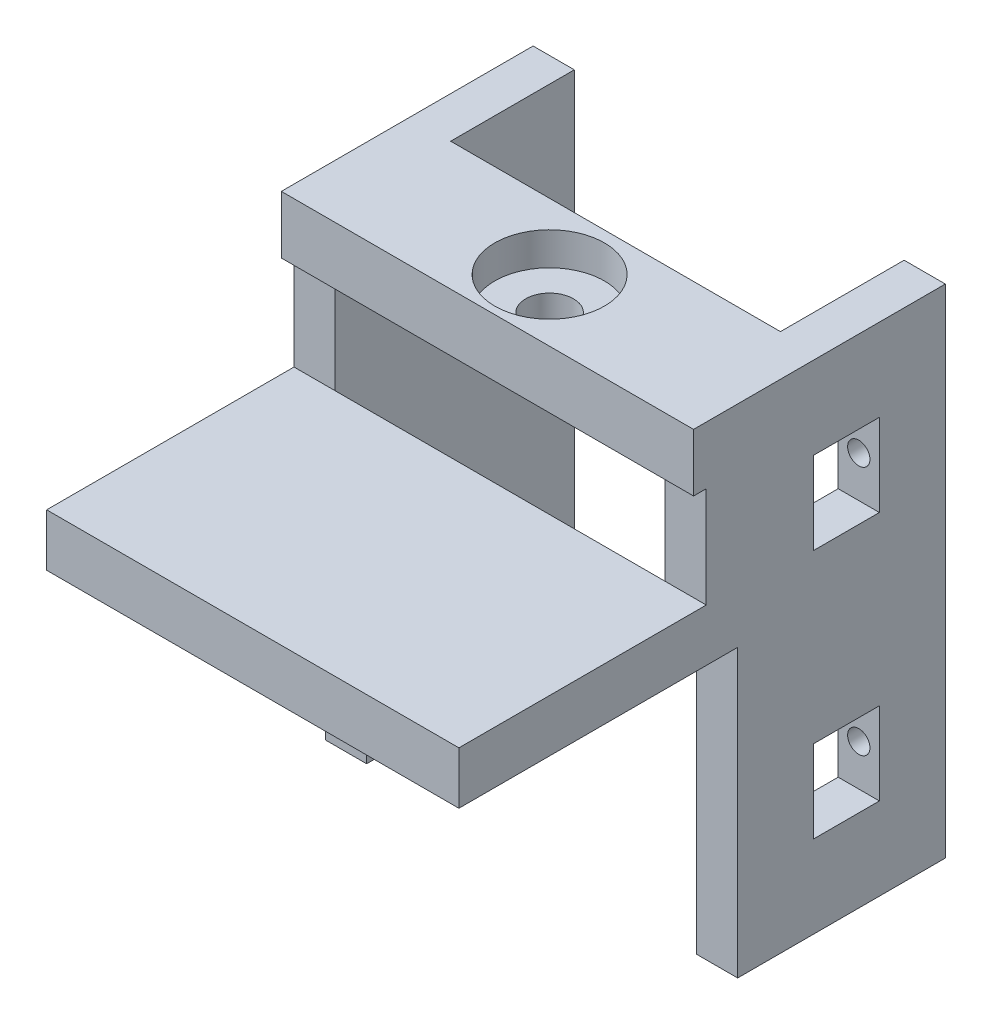
SolidWorks part; units mm, degrees
material "Copper"
ref_plane "Front Plane" through (0, 0, 0) normal (0, 0, 1) x (1, 0, 0)
ref_plane "Top Plane" through (0, 0, 0) normal (0, 1, 0) x (1, 0, 0)
ref_plane "Right Plane" through (0, 0, 0) normal (1, 0, 0) x (0, 0, -1)
sketch "Sketch1" plane through (0, 0, 0) normal (0, 1, 0) x (1, 0, 0)
  line L1 (0, 0) -> (50, 0)
  line L2 (0, 0) -> (0, 30)
  line L3 (0, 30) -> (50, 30)
  line L4 (50, 0) -> (50, 30)
  dimension "D1" = 50
  dimension "D2" = 30
extrude "Boss-Extrude1" add sketch "Sketch1" along normal blind 7
sketch "Sketch2" plane through (50, 0, 0) normal (1, 0, 0) x (0, 0, -1)
  line L0 (30, 7) -> (57, 7)
  line L1 (57, 7) -> (57, -53.3)
  line L2 (57, -53.3) -> (30, -53.3)
  line L3 (30, -53.3) -> (30, 7)
  dimension "D2" = 60.3
  dimension "D3" = 27
extrude "Boss-Extrude2" add sketch "Sketch2" against normal blind 5
ref_plane "Plane1" through (25, 0, 0) normal (1, 0, 0) x (0, 0, -1)
mirror "Mirror1" about plane through (25, 0, 0) normal (1, 0, 0) of "Boss-Extrude2"
sketch "Sketch3" plane through (0, 0, -30) normal (0, 0, -1) x (-1, 0, 0)
  line L4 (-5, 0) -> (-5, 7)
  line L5 (-5, 7) -> (-45, 7)
  line L6 (-45, 7) -> (-45, 0)
  line L7 (-45, 0) -> (-5, 0)
  line L8 (-5, 0) -> (-5, 7)
  line L9 (-5, 7) -> (-45, 7)
  line L10 (-45, 7) -> (-45, 0)
  line L11 (-45, 0) -> (-5, 0)
  dimension "D1" = 0
extrude "Boss-Extrude3" add sketch "Sketch3" along normal blind 12
sketch "Sketch4" plane through (0, 7, 0) normal (0, 1, 0) x (1, 0, 0)
  line L0 (25, 34) -> (25, 0) construction
  line L1 (0, 0) -> (50, 0) construction
  circle A0 centre (25, 34) radius 6.65
  dimension "D1" = 13.3
  dimension "D2" = 34
extrude "Cut-Extrude1" cut sketch "Sketch4" against normal blind 4
sketch "Sketch5" plane through (0, 3, 0) normal (0, 1, 0) x (1, 0, 0)
  circle A0 centre (25, 34) radius 2.9
  dimension "D1" = 5.8
extrude "Cut-Extrude2" cut sketch "Sketch5" against normal up to next
sketch "Sketch6" plane through (50, 0, 0) normal (1, 0, 0) x (0, 0, -1)
  line L0 (0, 7) -> (57, 7) construction
  line L1 (41, -3) -> (49, -3)
  line L2 (41, -3) -> (41, -13)
  line L3 (41, -13) -> (49, -13)
  line L4 (49, -3) -> (49, -13)
  line L5 (41, -33.3) -> (49, -33.3)
  line L6 (41, -33.3) -> (41, -43.3)
  line L7 (41, -43.3) -> (49, -43.3)
  line L8 (49, -33.3) -> (49, -43.3)
  line L9 (30, -53.3) -> (57, -53.3) construction
  line L10 (57, -53.3) -> (57, 7) construction
  dimension "D1" = 10
  dimension "D2" = 10
  dimension "D3" = 8
  dimension "D4" = 10
  dimension "D5" = 10
  dimension "D6" = 8
extrude "Cut-Extrude3" cut sketch "Sketch6" against normal through all
sketch "Sketch7" plane through (0, 0, -49) normal (0, 0, 1) x (1, 0, 0)
  line L0 (45, -33.3) -> (50, -43.3) construction
  line L1 (45, -3) -> (50, -13) construction
  line L2 (5, -13) -> (0, -3) construction
  line L3 (0, -33.3) -> (5, -43.3) construction
hole_wizard "#2 Clearance Hole1" positions "Sketch8" profile "Sketch9" hole size "#2" standard "ANSI Inch"
sketch "Sketch8" plane through (0, 0, -49) normal (0, 0, 1) x (1, 0, 0)
  line L0 (45, -33.3) -> (50, -43.3) construction
  line L1 (45, -3) -> (50, -13) construction
  line L2 (5, -13) -> (0, -3) construction
  line L3 (0, -33.3) -> (5, -43.3) construction
  point P0 (47.5, -38.3)
  point P4 (47.5, -8)
  point P8 (2.5, -8)
  point P12 (2.5, -38.3)
sketch "Sketch9" plane through (47.5, -38.3, -49) normal (1, 0, 0) x (0, -1, 0)
  line L0 (0, 0) -> (0, 8)
  line L1 (0, 8) -> (1.3525, 8)
  line L2 (1.3525, 8) -> (1.3525, 0)
  line L5 (1.3525, 0) -> (0, 0)
  line L11 (0, -6.35) -> (0, 107.95) construction
  dimension "Thru Hole Dia." = 2.7051
  dimension "Thru Hole Depth" = 8
sketch "Sketch10" plane through (0, 0, 0) normal (0, 0, 1) x (1, 0, 0)
  line L4 (0, 0) -> (50, 0)
  line L5 (50, 0) -> (50, 7)
  line L6 (50, 7) -> (0, 7)
  line L7 (0, 7) -> (0, 0)
  line L8 (0, 0) -> (50, 0)
  line L9 (50, 0) -> (50, 7)
  line L10 (50, 7) -> (0, 7)
  line L11 (0, 7) -> (0, 0)
  dimension "D1" = 0
extrude "Boss-Extrude4" add sketch "Sketch10" along normal blind 2
sketch "Sketch11" plane through (0, 0, -30) normal (0, 0, 1) x (1, 0, 0)
  line L4 (50, -53.3) -> (50, 0)
  line L5 (50, 0) -> (45, 0)
  line L6 (45, 0) -> (45, -53.3)
  line L7 (45, -53.3) -> (50, -53.3)
  line L8 (50, -53.3) -> (50, 0)
  line L9 (50, 0) -> (45, 0)
  line L10 (45, 0) -> (45, -53.3)
  line L11 (45, -53.3) -> (50, -53.3)
  line L12 (5, 0) -> (0, 0)
  line L13 (0, 0) -> (0, -53.3)
  line L14 (0, -53.3) -> (5, -53.3)
  line L15 (5, -53.3) -> (5, 0)
  line L16 (5, 0) -> (0, 0)
  line L17 (0, 0) -> (0, -53.3)
  line L18 (0, -53.3) -> (5, -53.3)
  line L19 (5, -53.3) -> (5, 0)
  dimension "D1" = 0
  dimension "D2" = 0
extrude "Boss-Extrude5" add sketch "Sketch11" along normal blind 2
sketch "Sketch13" plane through (0, 0, -28) normal (0, 0, 1) x (1, 0, 0)
  line L0 (45, -18.568) -> (50, -18.568)
  line L1 (45, 0) -> (45, -53.3) construction
  line L2 (50, -53.3) -> (50, 0) construction
  line L3 (5, -18.568) -> (0, -18.568)
  line L4 (5, -53.3) -> (5, 0) construction
  line L5 (0, 0) -> (0, -53.3) construction
  line L6 (45, -53.3) -> (50, -53.3) construction
  line L8 (45, -12.218) -> (50, -12.218)
  line L9 (5, -12.218) -> (0, -12.218)
  line L10 (45, -12.218) -> (45, -18.568)
  line L11 (50, -12.218) -> (50, -18.568)
  line L12 (5, -12.218) -> (5, -18.568)
  line L13 (0, -12.218) -> (0, -18.568)
  dimension "D1" = 34.732
  dimension "D2" = 6.35
extrude "Boss-Extrude6" add sketch "Sketch13" along normal blind 30
sketch "Sketch14" plane through (45, 0, 0) normal (-1, 0, 0) x (0, 0, 1)
  line L0 (-28, -12.218) -> (-28, -18.568)
  line L1 (-28, -18.568) -> (2, -18.568)
  line L2 (2, -18.568) -> (2, -12.218)
  line L3 (2, -12.218) -> (-28, -12.218)
extrude "Boss-Extrude7" add sketch "Sketch14" along normal up to vertex (40 mm away) up to point (5, -12.218, -28)
sketch "Sketch15" plane through (50, 0, 0) normal (1, 0, 0) x (0, 0, -1)
  line L0 (26.4628, 7) -> (26.4628, 0)
  line L1 (-2, 7) -> (57, 7) construction
  line L2 (-2, 0) -> (28, 0) construction
  line L3 (26.4628, 0) -> (-2, 0)
  line L4 (-2, 0) -> (-2, 7)
  line L5 (-2, 7) -> (26.4628, 7)
extrude "Cut-Extrude4" cut sketch "Sketch15" against normal through all
sketch "Sketch16" plane through (50, 0, 0) normal (1, 0, 0) x (0, 0, -1)
  line L0 (28, -53.3) -> (31.81, -53.3)
  line L1 (28, -53.3) -> (57, -53.3) construction
  line L2 (31.81, -53.3) -> (31.81, -18.568)
  line L3 (31.81, -18.568) -> (28, -18.568)
  line L4 (28, -18.568) -> (28, -53.3)
  dimension "D1" = 3.81
extrude "Cut-Extrude5" cut sketch "Sketch16" against normal through all
equation "\"D2@Sketch6\"=\"D1@Sketch6\""
